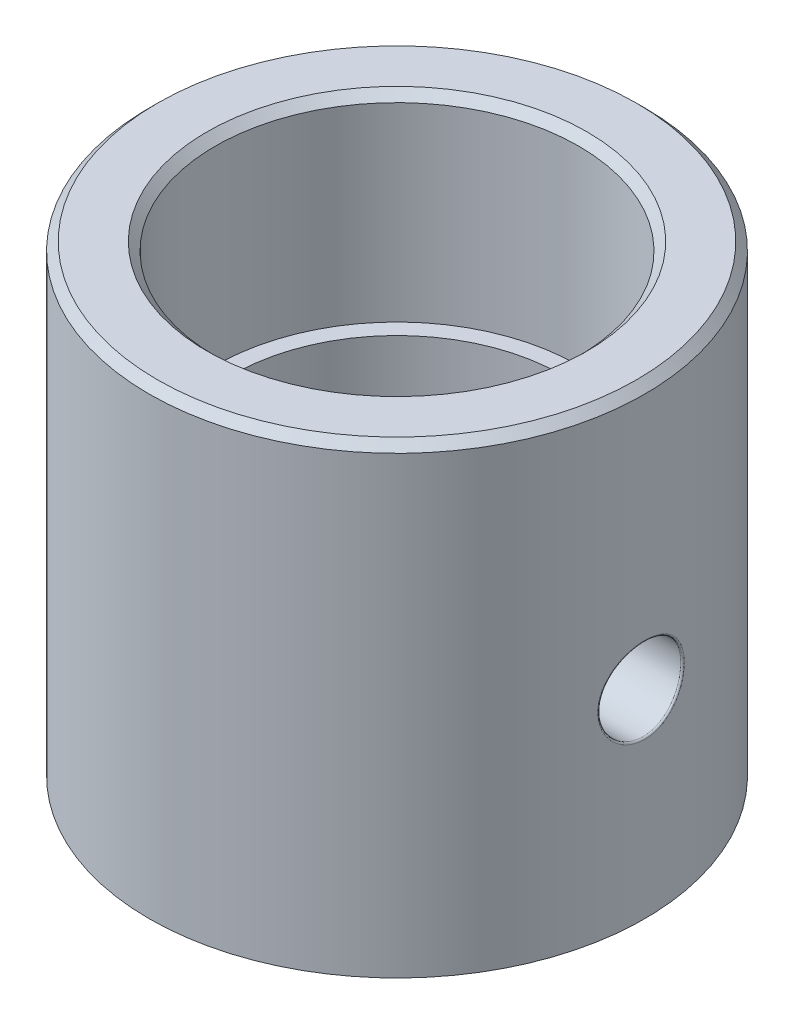
SolidWorks part; units mm, degrees
ref_plane "Front Plane" through (0, 0, 0) normal (0, 0, 1) x (1, 0, 0)
ref_plane "Top Plane" through (0, 0, 0) normal (0, 1, 0) x (1, 0, 0)
ref_plane "Right Plane" through (0, 0, 0) normal (1, 0, 0) x (0, 0, -1)
sketch "Sketch1" plane through (0, 0, 0) normal (0, 0, 1) x (1, 0, 0)
  line L0 (0, 0) -> (0, 27) construction
  line L1 (0, 0) -> (-15, 0)
  line L2 (-15, 0) -> (-15, 28)
  line L3 (-15, 28) -> (-11, 28)
  line L4 (-11, 28) -> (-11, 16)
  line L5 (-11, 16) -> (-10, 16)
  line L6 (-10, 16) -> (-10, 1)
  line L7 (-10, 1) -> (0, 1)
  line L8 (0, 1) -> (0, 0)
  point P2 (0, 27)
  point P4 (0, 0)
  point P8 (0, 0)
  dimension "D1" = 30
  dimension "D2" = 28
  dimension "D3" = 20
  dimension "D4" = 22
  dimension "D5" = 12
  dimension "D6" = 27
revolve "Revolve1" add sketch "Sketch1" angle 360 about L0
sketch "Sketch2" plane through (0, 0, 0) normal (1, 0, 0) x (0, 0, -1)
  line L0 (15, 28) -> (-15, 28) construction
  circle A0 centre (0, 12) radius 2.5
  point P2 (0, 0)
  dimension "D1" = 5
  dimension "D2" = 16
extrude "Cut-Extrude1" cut sketch "Sketch2" against normal through all both and the other way through all
chamfer "Chamfer1" distance 0.5 angle 45 2 edges at (0, 28, -15) (0, 28, -11)
fillet "Fillet1" radius 0.1 2 edges at (-14.9904, 14.4418, 0.5362) (14.7999, 12.5363, 2.4418)
